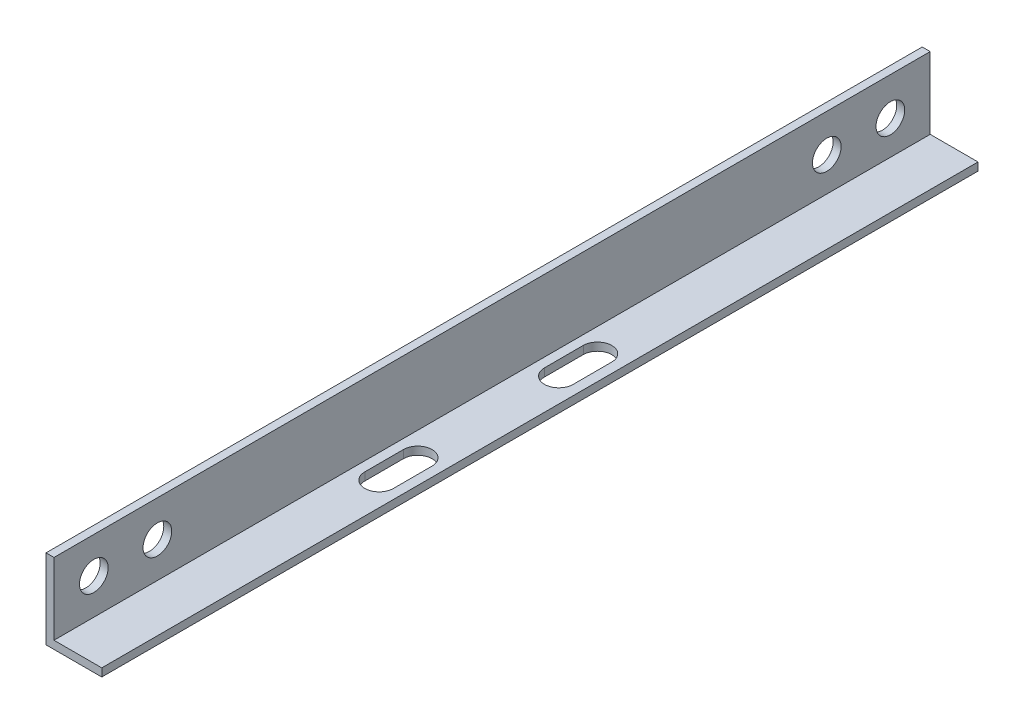
SolidWorks part; units mm, degrees
ref_plane "Front Plane" through (0, 0, 0) normal (0, 0, 1) x (1, 0, 0)
ref_plane "Top Plane" through (0, 0, 0) normal (0, 1, 0) x (1, 0, 0)
ref_plane "Right Plane" through (0, 0, 0) normal (1, 0, 0) x (0, 0, -1)
sketch "Sketch1" plane through (0, 0, 0) normal (0, 0, 1) x (1, 0, 0)
  line L0 (-9.2857, 23.8095) -> (-9.2857, -26.1905)
  line L1 (-9.2857, -26.1905) -> (25.7143, -26.1905)
  line L2 (25.7143, -26.1905) -> (25.7143, -21.1905)
  line L3 (25.7143, -21.1905) -> (-4.2857, -21.1905)
  line L4 (-4.2857, -21.1905) -> (-4.2857, 23.8095)
  line L5 (-4.2857, 23.8095) -> (-9.2857, 23.8095)
  dimension "D1" = 5
  dimension "D2" = 5
  dimension "D3" = 50
  dimension "D4" = 35
extrude "Boss-Extrude1" add sketch "Sketch1" along normal blind 549.91
sketch "Sketch2" plane through (-4.2857, 0, 0) normal (1, 0, 0) x (0, 0, -1)
  line L0 (-549.91, 1.3095) -> (0, 0) construction
  line L1 (-549.91, -21.1905) -> (-549.91, 23.8095) construction
  line L3 (0, -21.1905) -> (0, 23.8095) construction
  circle A0 centre (-524.91, 1.25) radius 9
  circle A1 centre (-485, 1.155) radius 9
  circle A10 centre (-64.91, 0.1546) radius 9
  circle A14 centre (-25, 0.0595) radius 9
  point P9 (0, 0)
  dimension "D1" = 25
  dimension "D3" = 460
  dimension "D2" = 39.91
  dimension "D4" = 25
extrude "Cut-Extrude1" cut sketch "Sketch2" against normal blind 10
sketch "Sketch3" plane through (0, -21.1905, 0) normal (0, 1, 0) x (1, 0, 0)
  line L0 (10.7143, -698.5) -> (10.7143, 0) construction
  line L6 (1.7335, -360.8843) -> (1.6974, -336.4658)
  line L7 (19.7335, -360.8843) -> (19.6951, -336.4658)
  line L8 (1.5825, -247.9236) -> (1.5464, -223.5051)
  line L9 (19.5825, -247.9236) -> (19.5441, -223.5051)
  line L16 (1.7335, -360.8843) -> (19.6951, -336.4658) construction
  line L17 (19.7335, -360.8843) -> (1.6974, -336.4658) construction
  line L18 (1.5825, -247.9236) -> (19.5441, -223.5051) construction
  line L19 (19.5825, -247.9236) -> (1.5464, -223.5051) construction
  arc A4 (1.7335, -360.8843) -> (19.7335, -360.8843) centre (10.7335, -360.8843) ccw
  arc A5 (1.6974, -336.4658) -> (19.6951, -336.4658) centre (10.6962, -336.6109) cw
  arc A6 (1.5825, -247.9236) -> (19.5825, -247.9236) centre (10.5825, -247.9236) ccw
  arc A7 (1.5464, -223.5051) -> (19.5441, -223.5051) centre (10.5452, -223.6503) cw
extrude "Cut-Extrude2" cut sketch "Sketch3" against normal blind 10
